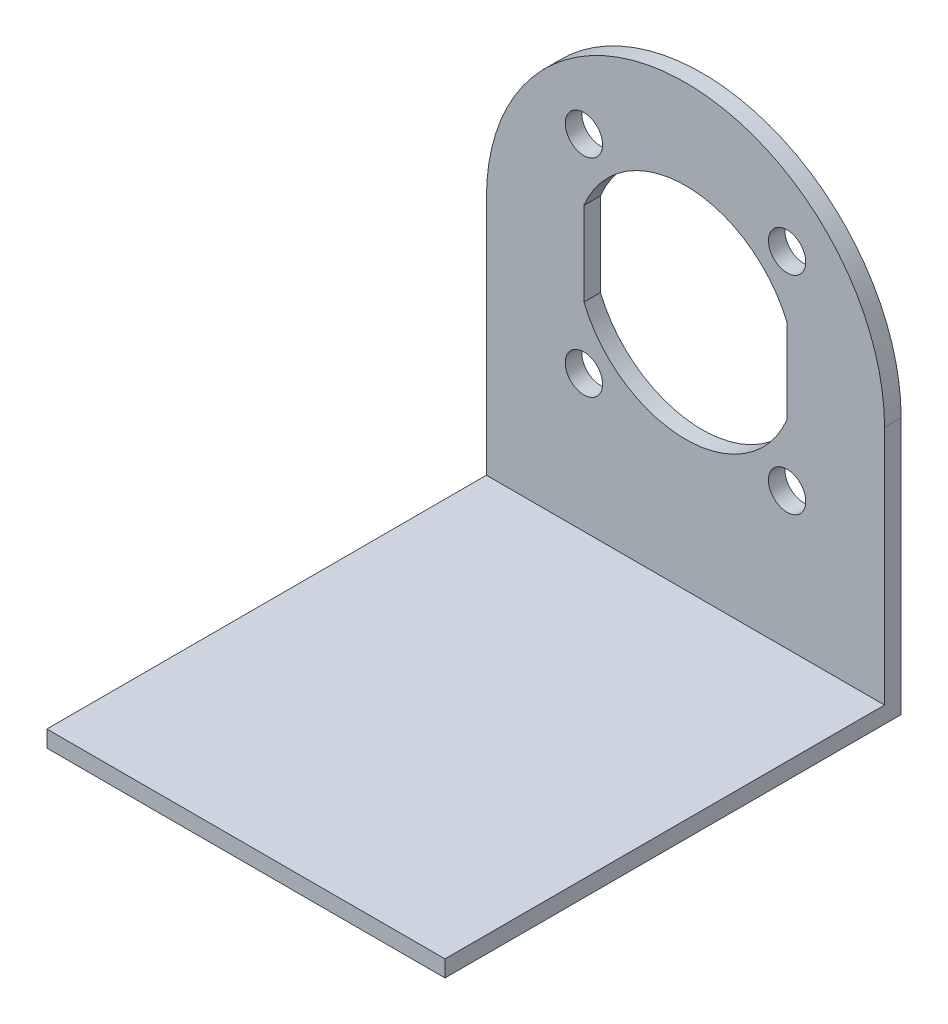
SolidWorks part; units mm, degrees
ref_plane "Front Plane" through (0, 0, 0) normal (0, 0, 1) x (1, 0, 0)
ref_plane "Top Plane" through (0, 0, 0) normal (0, 1, 0) x (1, 0, 0)
ref_plane "Right Plane" through (0, 0, 0) normal (1, 0, 0) x (0, 0, -1)
sketch "Sketch1" plane through (0, 0, 0) normal (0, 1, 0) x (1, 0, 0)
  line L1 (-38.7711, 34.1893) -> (9.2289, 34.1893)
  line L2 (-38.7711, 34.1893) -> (-38.7711, -20.8107)
  line L3 (-38.7711, -20.8107) -> (9.2289, -20.8107)
  line L4 (9.2289, 34.1893) -> (9.2289, -20.8107)
  dimension "D1" = 55
  dimension "D2" = 48
extrude "Boss-Extrude1" add sketch "Sketch1" along normal blind 2
sketch "Sketch2" plane through (0, 2, 0) normal (0, 1, 0) x (1, 0, 0)
  line L0 (9.2289, -20.8107) -> (9.2289, 34.1893) construction
  line L1 (-38.7711, 34.1893) -> (9.2289, 34.1893)
  line L2 (-38.7711, 34.1893) -> (-38.7711, 32.1893)
  line L3 (-38.7711, 32.1893) -> (9.2289, 32.1893)
  line L4 (9.2289, 34.1893) -> (9.2289, 32.1893)
  dimension "D1" = 2
extrude "Boss-Extrude2" add sketch "Sketch2" along normal blind 53
sketch "Sketch3" plane through (0, 0, -32.1893) normal (0, 0, 1) x (1, 0, 0)
  line L3 (-38.7711, 55) -> (9.2289, 55)
  line L4 (-38.7711, 55) -> (-38.7711, 31)
  line L6 (9.2289, 55) -> (9.2289, 31)
  arc A0 (9.2289, 31) -> (-38.7711, 31) centre (-14.7711, 31) ccw
  line M3 (9.2289, 2) -> (9.2289, 55)
  line M4 (9.2289, 55) -> (-38.7711, 55)
  line M5 (-38.7711, 55) -> (-38.7711, 2)
extrude "Cut-Extrude1" cut sketch "Sketch3" against normal blind 53 contours A0 L3 M5 | A0 M3 M4
sketch "Sketch4" plane through (0, 0, -32.1893) normal (0, 0, 1) x (1, 0, 0)
  line L1 (-27.0211, 25.9502) -> (-27.0211, 36.0498)
  line L2 (-2.5211, 25.9502) -> (-2.5211, 36.0498)
  arc A0 (-27.0211, 25.9502) -> (-2.5211, 25.9502) centre (-14.7711, 31) ccw
  arc A1 (-2.5211, 36.0498) -> (-27.0211, 36.0498) centre (-14.7711, 31) ccw
  point P4 (-14.7711, 31)
  point P8 (-14.7711, 31)
  point P10 (-27.0211, 31)
  point P13 (-2.5211, 31)
extrude "Cut-Extrude2" cut sketch "Sketch4" against normal blind 53 contours L2 A1 L1 A0
sketch "Sketch5" plane through (0, 0, -32.1893) normal (0, 0, 1) x (1, 0, 0)
  circle A0 centre (-14.7711, 31) radius 17.5 construction
  circle A1 centre (-27.0211, 43.4975) radius 2.25
  circle A2 centre (-2.5211, 43.4975) radius 2.25
  circle A3 centre (-27.0211, 18.5025) radius 2.25
  circle A4 centre (-2.5211, 18.5025) radius 2.25
  point P6 (-27.0211, 31)
  point P9 (-2.5211, 31)
  dimension "D1" = 35
  dimension "D2" = 4.5
  dimension "D3" = 4.5
  dimension "D4" = 4.5
  dimension "D5" = 4.5
extrude "Cut-Extrude3" cut sketch "Sketch5" against normal blind 53
